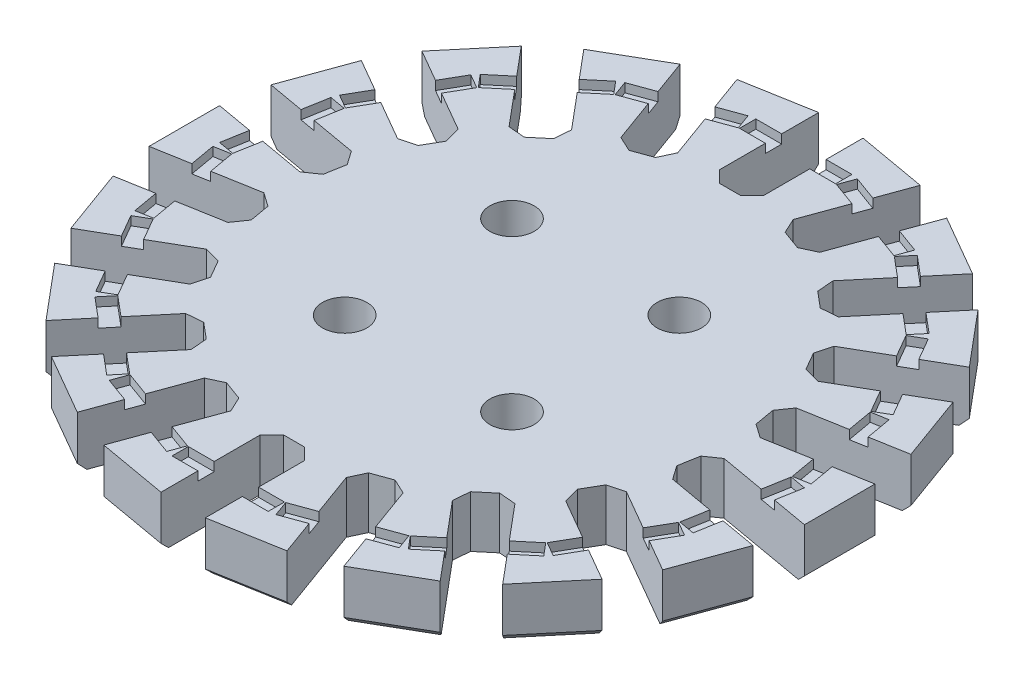
SolidWorks part; units mm, degrees
ref_plane "Front Plane" through (0, 0, 0) normal (0, 0, 1) x (1, 0, 0)
ref_plane "Top Plane" through (0, 0, 0) normal (0, 1, 0) x (1, 0, 0)
ref_plane "Right Plane" through (0, 0, 0) normal (1, 0, 0) x (0, 0, -1)
sketch "Sketch1" plane through (0, 0, 0) normal (0, 1, 0) x (1, 0, 0)
  line L0 (-1.5, 22.2355) -> (-1.5, 14.7355)
  line L1 (-1.5, 22.2355) -> (-6.1955, 21.4076)
  line L2 (-9.0145, 20.3815) -> (-13.1436, 17.9976)
  line L3 (-15.4418, 16.0692) -> (-18.5065, 12.4168)
  line L4 (-20.0065, 9.8187) -> (-21.6372, 5.3384)
  line L5 (-22.1582, 2.3839) -> (-22.1582, -2.3839)
  line L6 (-21.6372, -5.3384) -> (-20.0065, -9.8187)
  line L7 (-18.5065, -12.4168) -> (-15.4418, -16.0692)
  line L8 (-13.1436, -17.9976) -> (-9.0145, -20.3815)
  line L9 (-6.1955, -21.4076) -> (-1.5, -22.2355)
  line L10 (1.5, -22.2355) -> (6.1955, -21.4076)
  line L11 (9.0145, -20.3815) -> (13.1436, -17.9976)
  line L12 (15.4418, -16.0692) -> (18.5065, -12.4168)
  line L13 (20.0065, -9.8187) -> (21.6372, -5.3384)
  line L14 (22.1582, -2.3839) -> (22.1582, 2.3839)
  line L15 (21.6372, 5.3384) -> (20.0065, 9.8187)
  line L16 (18.5065, 12.4168) -> (15.4418, 16.0692)
  line L17 (13.1436, 17.9976) -> (9.0145, 20.3815)
  line L18 (6.1955, 21.4076) -> (1.5, 22.2355)
  line L19 (-1.5, 14.7355) -> (1.5, 14.7355)
  line L20 (1.5, 14.7355) -> (1.5, 22.2355)
  line L21 (6.4494, 13.3338) -> (9.0145, 20.3815)
  line L22 (3.6303, 14.3599) -> (6.4494, 13.3338)
  line L23 (6.1955, 21.4076) -> (3.6303, 14.3599)
  line L24 (10.6209, 10.3239) -> (15.4418, 16.0692)
  line L25 (8.3227, 12.2522) -> (10.6209, 10.3239)
  line L26 (13.1436, 17.9976) -> (8.3227, 12.2522)
  line L27 (13.5113, 6.0687) -> (20.0065, 9.8187)
  line L28 (12.0113, 8.6668) -> (13.5113, 6.0687)
  line L29 (18.5065, 12.4168) -> (12.0113, 8.6668)
  line L30 (14.7721, 1.0816) -> (22.1582, 2.3839)
  line L31 (14.2512, 4.036) -> (14.7721, 1.0816)
  line L32 (21.6372, 5.3384) -> (14.2512, 4.036)
  line L33 (14.2512, -4.036) -> (21.6372, -5.3384)
  line L34 (14.7721, -1.0816) -> (14.2512, -4.036)
  line L35 (22.1582, -2.3839) -> (14.7721, -1.0816)
  line L36 (12.0113, -8.6668) -> (18.5065, -12.4168)
  line L37 (13.5113, -6.0687) -> (12.0113, -8.6668)
  line L38 (20.0065, -9.8187) -> (13.5113, -6.0687)
  line L39 (8.3227, -12.2522) -> (13.1436, -17.9976)
  line L40 (10.6209, -10.3239) -> (8.3227, -12.2522)
  line L41 (15.4418, -16.0692) -> (10.6209, -10.3239)
  line L42 (3.6303, -14.3599) -> (6.1955, -21.4076)
  line L43 (6.4494, -13.3338) -> (3.6303, -14.3599)
  line L44 (9.0145, -20.3815) -> (6.4494, -13.3338)
  line L45 (-1.5, -14.7355) -> (-1.5, -22.2355)
  line L46 (1.5, -14.7355) -> (-1.5, -14.7355)
  line L47 (1.5, -22.2355) -> (1.5, -14.7355)
  line L48 (-6.4494, -13.3338) -> (-9.0145, -20.3815)
  line L49 (-3.6303, -14.3599) -> (-6.4494, -13.3338)
  line L50 (-6.1955, -21.4076) -> (-3.6303, -14.3599)
  line L51 (-10.6209, -10.3239) -> (-15.4418, -16.0692)
  line L52 (-8.3227, -12.2522) -> (-10.6209, -10.3239)
  line L53 (-13.1436, -17.9976) -> (-8.3227, -12.2522)
  line L54 (-13.5113, -6.0687) -> (-20.0065, -9.8187)
  line L55 (-12.0113, -8.6668) -> (-13.5113, -6.0687)
  line L56 (-18.5065, -12.4168) -> (-12.0113, -8.6668)
  line L57 (-14.7721, -1.0816) -> (-22.1582, -2.3839)
  line L58 (-14.2512, -4.036) -> (-14.7721, -1.0816)
  line L59 (-21.6372, -5.3384) -> (-14.2512, -4.036)
  line L60 (-14.2512, 4.036) -> (-21.6372, 5.3384)
  line L61 (-14.7721, 1.0816) -> (-14.2512, 4.036)
  line L62 (-22.1582, 2.3839) -> (-14.7721, 1.0816)
  line L63 (-12.0113, 8.6668) -> (-18.5065, 12.4168)
  line L64 (-13.5113, 6.0687) -> (-12.0113, 8.6668)
  line L65 (-20.0065, 9.8187) -> (-13.5113, 6.0687)
  line L66 (-8.3227, 12.2522) -> (-13.1436, 17.9976)
  line L67 (-10.6209, 10.3239) -> (-8.3227, 12.2522)
  line L68 (-15.4418, 16.0692) -> (-10.6209, 10.3239)
  line L69 (-3.6303, 14.3599) -> (-6.1955, 21.4076)
  line L70 (-6.4494, 13.3338) -> (-3.6303, 14.3599)
  line L71 (-9.0145, 20.3815) -> (-6.4494, 13.3338)
  arc A0 (6.1516, 21.2871) -> (1.5, 22.1073) centre (0, 0) ccw construction
  arc A1 (13.0613, 17.8994) -> (8.9707, 20.2611) centre (0, 0) ccw construction
  arc A2 (18.3955, 12.3527) -> (15.3594, 15.971) centre (0, 0) ccw construction
  arc A3 (21.511, 5.3161) -> (19.8955, 9.7546) centre (0, 0) ccw construction
  arc A4 (22.032, -2.3617) -> (22.032, 2.3617) centre (0, 0) ccw construction
  arc A5 (19.8955, -9.7546) -> (21.511, -5.3161) centre (0, 0) ccw construction
  arc A6 (-8.9707, 20.2611) -> (-13.0613, 17.8994) centre (0, 0) ccw construction
  arc A7 (-15.3594, 15.971) -> (-18.3955, 12.3527) centre (0, 0) ccw construction
  arc A8 (-19.8955, 9.7546) -> (-21.511, 5.3161) centre (0, 0) ccw construction
  arc A9 (-22.032, 2.3617) -> (-22.032, -2.3617) centre (0, 0) ccw construction
  arc A10 (-21.511, -5.3161) -> (-19.8955, -9.7546) centre (0, 0) ccw construction
  arc A11 (-18.3955, -12.3527) -> (-15.3594, -15.971) centre (0, 0) ccw construction
  arc A12 (-13.0613, -17.8994) -> (-8.9707, -20.2611) centre (0, 0) ccw construction
  arc A13 (-6.1516, -21.2871) -> (-1.5, -22.1073) centre (0, 0) ccw construction
  arc A14 (1.5, -22.1073) -> (6.1516, -21.2871) centre (0, 0) ccw construction
  arc A15 (8.9707, -20.2611) -> (13.0613, -17.8994) centre (0, 0) ccw construction
  arc A16 (15.3594, -15.971) -> (18.3955, -12.3527) centre (0, 0) ccw construction
  arc A17 (-1.5, 22.1073) -> (-6.1516, 21.2871) centre (0, 0) ccw construction
  point P96 (0, 0)
  dimension "D1" = 44.3163
  dimension "D2" = 3
  dimension "D3" = 1.5
  dimension "D4" = 7.5
  dimension "D5" = 18
extrude "Boss-Extrude1" add sketch "Sketch1" along normal blind 3.5
chamfer "Chamfer1" distance 0.8 angle 45 36 edges at (-10.6209, 1.75, 10.3239) (-8.3227, 1.75, 12.2522) (-3.6303, 1.75, 14.3599) (1.5, 1.75, 14.7355) (6.4494, 1.75, 13.3338) (10.6209, 1.75, 10.3239) (13.5113, 1.75, 6.0687) (-6.4494, 1.75, 13.3338) (-1.5, 1.75, 14.7355) (3.6303, 1.75, 14.3599) (8.3227, 1.75, 12.2522) (12.0113, 1.75, 8.6668) (14.7721, 1.75, 1.0816) (14.2512, 1.75, -4.036) (12.0113, 1.75, -8.6668) (8.3227, 1.75, -12.2522) (14.2512, 1.75, 4.036) (14.7721, 1.75, -1.0816) (13.5113, 1.75, -6.0687) (10.6209, 1.75, -10.3239) (3.6303, 1.75, -14.3599) (-1.5, 1.75, -14.7355) (-13.5113, 1.75, -6.0687) (-10.6209, 1.75, -10.3239) (-6.4494, 1.75, -13.3338) (1.5, 1.75, -14.7355) (-3.6303, 1.75, -14.3599) (-8.3227, 1.75, -12.2522) (-12.0113, 1.75, -8.6668) (-14.7721, 1.75, -1.0816) (-14.2512, 1.75, -4.036) (-14.2512, 1.75, 4.036) (-14.7721, 1.75, 1.0816) (-12.0113, 1.75, 8.6668) (-13.5113, 1.75, 6.0687) (6.4494, 1.75, -13.3338)
sketch "Sketch2" plane through (0, 3.5, 0) normal (0, 1, 0) x (1, 0, 0)
  line L0 (-3.25, 19.7355) -> (3.25, 19.7355)
  line L2 (3.25, 19.7355) -> (3.25, 18.6355)
  line L3 (3.25, 18.6355) -> (-3.25, 18.6355)
  line L4 (-3.25, 18.6355) -> (-3.25, 19.7355)
  line L72 (3.3197, 18.6232) -> (3.6959, 19.6569)
  line L73 (3.6959, 19.6569) -> (9.8039, 17.4337)
  line L74 (9.8039, 17.4337) -> (9.4277, 16.4001)
  line L75 (9.4277, 16.4001) -> (3.3197, 18.6232)
  line L76 (9.489, 16.3647) -> (10.1961, 17.2073)
  line L77 (10.1961, 17.2073) -> (15.1754, 13.0292)
  line L78 (15.1754, 13.0292) -> (14.4683, 12.1866)
  line L79 (14.4683, 12.1866) -> (9.489, 16.3647)
  line L80 (14.5138, 12.1323) -> (15.4665, 12.6823)
  line L81 (15.4665, 12.6823) -> (18.7165, 7.0532)
  line L82 (18.7165, 7.0532) -> (17.7638, 6.5032)
  line L83 (17.7638, 6.5032) -> (14.5138, 12.1323)
  line L84 (17.788, 6.4366) -> (18.8713, 6.6277)
  line L85 (18.8713, 6.6277) -> (20, 0.2264)
  line L86 (20, 0.2264) -> (18.9168, 0.0354)
  line L87 (18.9168, 0.0354) -> (17.788, 6.4366)
  line L88 (18.9168, -0.0354) -> (20, -0.2264)
  line L89 (20, -0.2264) -> (18.8713, -6.6277)
  line L90 (18.8713, -6.6277) -> (17.788, -6.4366)
  line L91 (17.788, -6.4366) -> (18.9168, -0.0354)
  line L92 (17.7638, -6.5032) -> (18.7165, -7.0532)
  line L93 (18.7165, -7.0532) -> (15.4665, -12.6823)
  line L94 (15.4665, -12.6823) -> (14.5138, -12.1323)
  line L95 (14.5138, -12.1323) -> (17.7638, -6.5032)
  line L96 (14.4683, -12.1866) -> (15.1754, -13.0292)
  line L97 (15.1754, -13.0292) -> (10.1961, -17.2073)
  line L98 (10.1961, -17.2073) -> (9.489, -16.3647)
  line L99 (9.489, -16.3647) -> (14.4683, -12.1866)
  line L100 (9.4277, -16.4001) -> (9.8039, -17.4337)
  line L101 (9.8039, -17.4337) -> (3.6959, -19.6569)
  line L102 (3.6959, -19.6569) -> (3.3197, -18.6232)
  line L103 (3.3197, -18.6232) -> (9.4277, -16.4001)
  line L104 (3.25, -18.6355) -> (3.25, -19.7355)
  line L105 (3.25, -19.7355) -> (-3.25, -19.7355)
  line L106 (-3.25, -19.7355) -> (-3.25, -18.6355)
  line L107 (-3.25, -18.6355) -> (3.25, -18.6355)
  line L108 (-3.3197, -18.6232) -> (-3.6959, -19.6569)
  line L109 (-3.6959, -19.6569) -> (-9.8039, -17.4337)
  line L110 (-9.8039, -17.4337) -> (-9.4277, -16.4001)
  line L111 (-9.4277, -16.4001) -> (-3.3197, -18.6232)
  line L112 (-9.489, -16.3647) -> (-10.1961, -17.2073)
  line L113 (-10.1961, -17.2073) -> (-15.1754, -13.0292)
  line L114 (-15.1754, -13.0292) -> (-14.4683, -12.1866)
  line L115 (-14.4683, -12.1866) -> (-9.489, -16.3647)
  line L116 (-14.5138, -12.1323) -> (-15.4665, -12.6823)
  line L117 (-15.4665, -12.6823) -> (-18.7165, -7.0532)
  line L118 (-18.7165, -7.0532) -> (-17.7638, -6.5032)
  line L119 (-17.7638, -6.5032) -> (-14.5138, -12.1323)
  line L120 (-17.788, -6.4366) -> (-18.8713, -6.6277)
  line L121 (-18.8713, -6.6277) -> (-20, -0.2264)
  line L122 (-20, -0.2264) -> (-18.9168, -0.0354)
  line L123 (-18.9168, -0.0354) -> (-17.788, -6.4366)
  line L124 (-18.9168, 0.0354) -> (-20, 0.2264)
  line L125 (-20, 0.2264) -> (-18.8713, 6.6277)
  line L126 (-18.8713, 6.6277) -> (-17.788, 6.4366)
  line L127 (-17.788, 6.4366) -> (-18.9168, 0.0354)
  line L128 (-17.7638, 6.5032) -> (-18.7165, 7.0532)
  line L129 (-18.7165, 7.0532) -> (-15.4665, 12.6823)
  line L130 (-15.4665, 12.6823) -> (-14.5138, 12.1323)
  line L131 (-14.5138, 12.1323) -> (-17.7638, 6.5032)
  line L132 (-14.4683, 12.1866) -> (-15.1754, 13.0292)
  line L133 (-15.1754, 13.0292) -> (-10.1961, 17.2073)
  line L134 (-10.1961, 17.2073) -> (-9.489, 16.3647)
  line L135 (-9.489, 16.3647) -> (-14.4683, 12.1866)
  line L136 (-9.4277, 16.4001) -> (-9.8039, 17.4337)
  line L137 (-9.8039, 17.4337) -> (-3.6959, 19.6569)
  line L138 (-3.6959, 19.6569) -> (-3.3197, 18.6232)
  line L139 (-3.3197, 18.6232) -> (-9.4277, 16.4001)
  line L140 (-22.1582, 2.3839) -> (-22.1582, -2.3839) construction
  point P76 (0, 0)
  dimension "D1" = 6.5
  dimension "D2" = 2.5
  dimension "D3" = 3.25
  dimension "D4" = 1.1
  dimension "D6" = 2.1581
  dimension "D7" = 18.6355
  dimension "D5" = 18
extrude "Cut-Extrude1" cut sketch "Sketch2" against normal blind 0.6
chamfer "Chamfer2" distance 0.5 angle 45 18 edges at (-11.0791, 0, 19.1895) (-16.9741, 0, 14.243) (-20.8219, 0, 7.5785) (-22.1582, 0, 0) (-20.8219, 0, -7.5785) (-16.9741, 0, -14.243) (-11.0791, 0, -19.1895) (-3.8477, 0, -21.8215) (3.8477, 0, -21.8215) (11.0791, 0, -19.1895) (16.9741, 0, -14.243) (20.8219, 0, -7.5785) (22.1582, 0, 0) (20.8219, 0, 7.5785) (16.9741, 0, 14.243) (11.0791, 0, 19.1895) (-3.8477, 0, 21.8215) (3.8477, 0, 21.8215)
sketch "Sketch4" plane through (0, 0, 0) normal (0, -1, 0) x (1, 0, 0)
  line L1 (-5.6569, -5.6569) -> (5.6569, -5.6569) construction
  line L2 (-5.6569, -5.6569) -> (-5.6569, 5.6569) construction
  line L3 (-5.6569, 5.6569) -> (5.6569, 5.6569) construction
  line L4 (5.6569, -5.6569) -> (5.6569, 5.6569) construction
  line L5 (-5.6569, -5.6569) -> (5.6569, 5.6569) construction
  line L6 (-5.6569, 5.6569) -> (5.6569, -5.6569) construction
  circle A8 centre (-5.6569, 5.6569) radius 1.5
  circle A9 centre (5.6569, 5.6569) radius 1.5
  circle A10 centre (5.6569, -5.6569) radius 1.5
  circle A11 centre (-5.6569, -5.6569) radius 1.5
  point P0 (0, 0)
  dimension "D1" = 16
  dimension "D2" = 3
extrude "Cut-Extrude4" cut sketch "Sketch4" against normal up to surface (3.5 mm away) up to face at (0, 3.5, 0)
sketch "Sketch5" plane through (0, 0, 0) normal (0, -1, 0) x (1, 0, 0)
  circle A0 centre (-5.6569, 5.6569) radius 3
  circle A2 centre (5.6569, -5.6569) radius 3
  circle A3 centre (-5.6569, -5.6569) radius 3
  circle A4 centre (5.6569, 5.6569) radius 3
  dimension "D1" = 6
extrude "Cut-Extrude5" cut sketch "Sketch5" against normal blind 1.1
